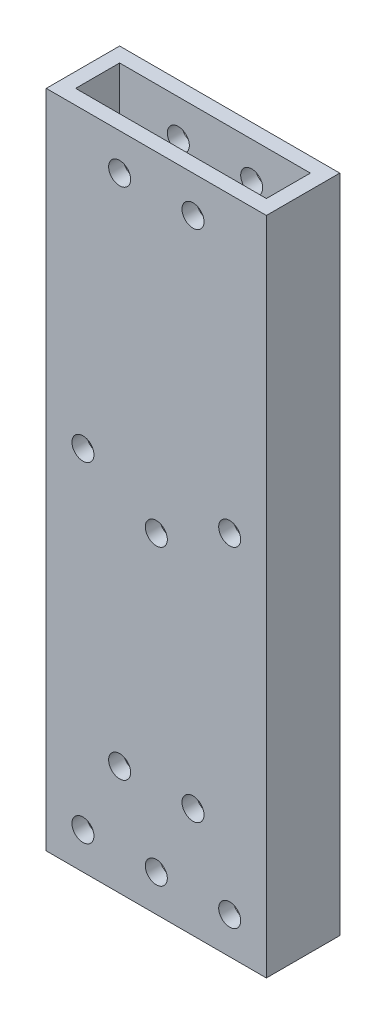
SolidWorks part; units mm, degrees
ref_plane "前视基准面" through (0, 0, 0) normal (0, 0, 1) x (1, 0, 0)
ref_plane "上视基准面" through (0, 0, 0) normal (0, 1, 0) x (1, 0, 0)
ref_plane "右视基准面" through (0, 0, 0) normal (1, 0, 0) x (0, 0, -1)
sketch "草图1" plane through (0, 0, 0) normal (0, 1, 0) x (1, 0, 0)
  line L1 (-15, 5) -> (15, 5)
  line L2 (-15, 5) -> (-15, -5)
  line L3 (-15, -5) -> (15, -5)
  line L4 (15, 5) -> (15, -5)
  line L5 (-15, 5) -> (15, -5) construction
  line L6 (-15, -5) -> (15, 5) construction
  line L7 (-13, 3) -> (13, 3)
  line L8 (-13, 3) -> (-13, -3)
  line L9 (-13, -3) -> (13, -3)
  line L10 (13, 3) -> (13, -3)
  line L11 (-13, 3) -> (13, -3) construction
  line L12 (-13, -3) -> (13, 3) construction
  point P0 (0, 0)
  point P6 (0, 0)
  dimension "D1" = 30
  dimension "D2" = 10
  dimension "D3" = 2
  dimension "D4" = 2
extrude "凸台-拉伸1" add sketch "草图1" along normal mid plane 90
sketch "草图2" plane through (0, 0, 5) normal (0, 0, 1) x (1, 0, 0)
  circle A0 centre (5, 40) radius 1.5
  circle A1 centre (10, 5) radius 1.5
  circle A2 centre (0, 0) radius 1.5
  circle A3 centre (-10, 5) radius 1.5
  circle A4 centre (-5, 40) radius 1.5
  circle A5 centre (5, -30) radius 1.5
  circle A6 centre (-5, -30) radius 1.5
  circle A7 centre (-10, -40) radius 1.5
  circle A8 centre (0, -40) radius 1.5
  circle A9 centre (10, -40) radius 1.5
extrude "切除-拉伸1" cut sketch "草图2" against normal through all
